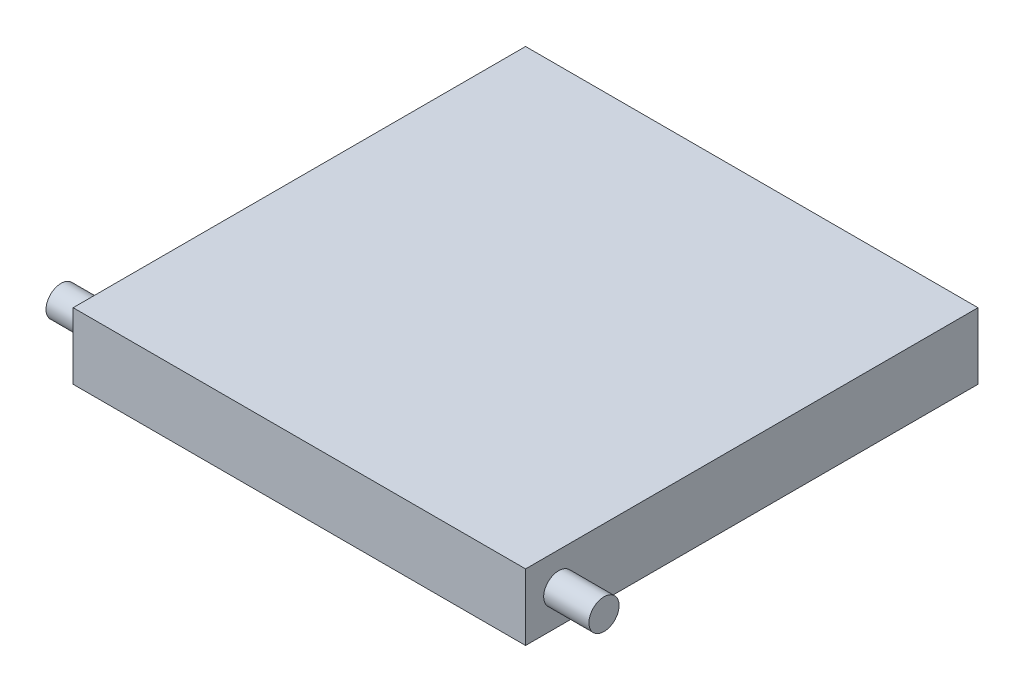
SolidWorks part; units mm, degrees
ref_plane "Plan de face" through (0, 0, 0) normal (0, 0, 1) x (1, 0, 0)
ref_plane "Plan de dessus" through (0, 0, 0) normal (0, 1, 0) x (1, 0, 0)
ref_plane "Plan de droite" through (0, 0, 0) normal (1, 0, 0) x (0, 0, -1)
sketch "Esquisse1" plane through (0, 0, 0) normal (0, 1, 0) x (1, 0, 0)
  line L1 (-75, -75) -> (75, -75)
  line L2 (-75, -75) -> (-75, 75)
  line L3 (-75, 75) -> (75, 75)
  line L4 (75, -75) -> (75, 75)
  line L5 (-75, -75) -> (75, 75) construction
  line L6 (-75, 75) -> (75, -75) construction
  point P0 (0, 0)
  dimension "D1" = 150
  dimension "D2" = 150
extrude "Boss.-Extru.1" add sketch "Esquisse1" along normal blind 22
sketch "Esquisse2" plane through (75, 0, 0) normal (1, 0, 0) x (0, 0, -1)
  line L0 (-75, 0) -> (-64, 0)
  line L1 (-75, 0) -> (75, 0) construction
  line L2 (-64, 0) -> (-64, 22) construction
  line L3 (-75, 22) -> (75, 22) construction
  circle A0 centre (-64, 11) radius 5
  dimension "D2" = 10
  dimension "D1" = 11
extrude "Boss.-Extru.2" add sketch "Esquisse2" along normal blind 15 contours L2 A0 | L2 A0
sketch "Esquisse6" plane through (-75, 0, 0) normal (-1, 0, 0) x (0, 0, 1)
  circle A0 centre (64, 11) radius 5
  dimension "D1" = 10
extrude "Boss.-Extru.3" add sketch "Esquisse6" along normal blind 15
